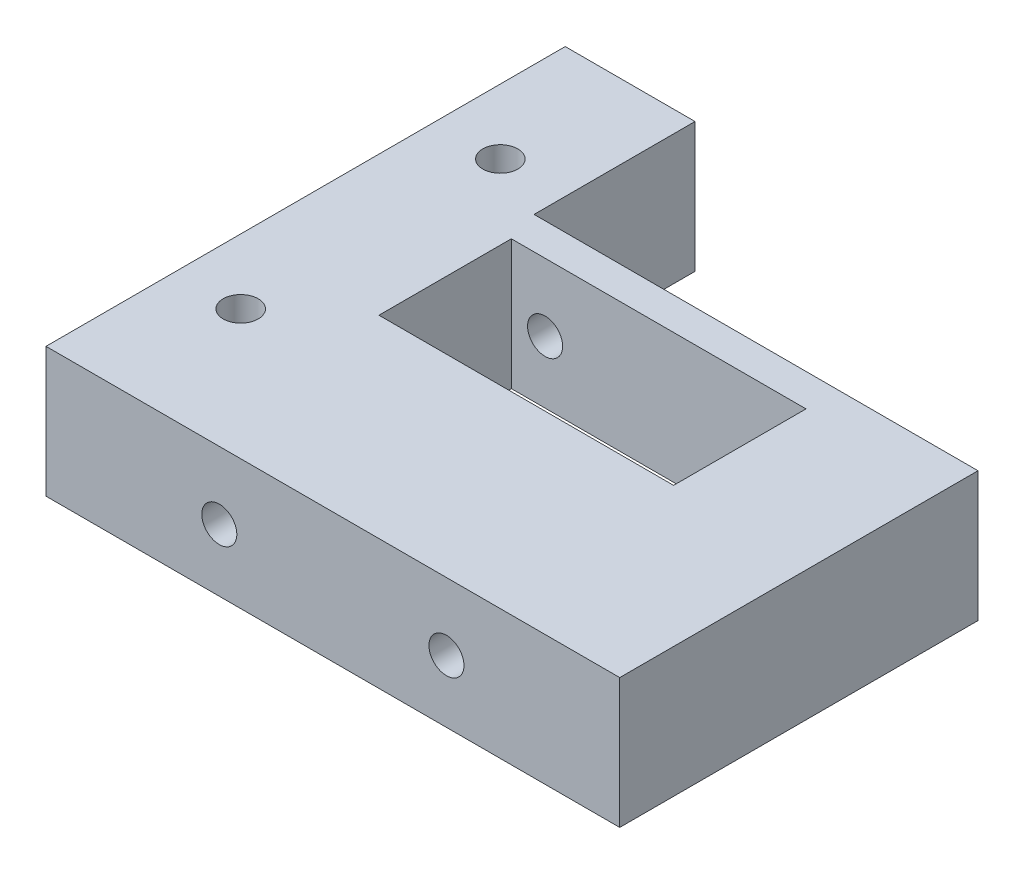
SolidWorks part; units mm, degrees
ref_plane "Front Plane" through (0, 0, 0) normal (0, 0, 1) x (1, 0, 0)
ref_plane "Top Plane" through (0, 0, 0) normal (0, 1, 0) x (1, 0, 0)
ref_plane "Right Plane" through (0, 0, 0) normal (1, 0, 0) x (0, 0, -1)
sketch "Sketch1" plane through (0, 0, 0) normal (0, 1, 0) x (1, 0, 0)
  line L1 (56.134, 50.8) -> (-56.134, 50.8)
  line L2 (56.134, 50.8) -> (56.134, -50.8)
  line L3 (56.134, -50.8) -> (-56.134, -50.8)
  line L4 (-56.134, 50.8) -> (-56.134, -50.8)
  line L5 (56.134, 50.8) -> (-56.134, -50.8) construction
  line L6 (56.134, -50.8) -> (-56.134, 50.8) construction
  line L7 (28.829, 12.954) -> (-28.829, 12.954)
  line L8 (28.829, 12.954) -> (28.829, -12.954)
  line L9 (28.829, -12.954) -> (-28.829, -12.954)
  line L10 (-28.829, 12.954) -> (-28.829, -12.954)
  line L11 (28.829, 12.954) -> (-28.829, -12.954) construction
  line L12 (28.829, -12.954) -> (-28.829, 12.954) construction
  point P0 (0, 0)
  point P6 (0, 0)
  dimension "D1" = 56.134
  dimension "D2" = 101.6
  dimension "D3" = 25.908
  dimension "D4" = 57.658
extrude "Boss-Extrude1" add sketch "Sketch1" along normal blind 25.4
sketch "Sketch2" plane through (0, 0, 0) normal (0, 1, 0) x (1, 0, 0)
  line L0 (56.134, 50.8) -> (-56.134, 50.8) construction
  line L1 (-30.734, 50.8) -> (56.134, 50.8)
  line L2 (-30.734, 50.8) -> (-30.734, 19.304)
  line L3 (-30.734, 19.304) -> (56.134, 19.304)
  line L4 (56.134, 50.8) -> (56.134, 19.304)
  line L5 (56.134, -50.8) -> (56.134, 50.8) construction
  line L6 (28.829, 12.954) -> (-28.829, 12.954) construction
  line L7 (-56.134, 50.8) -> (-56.134, -50.8) construction
  dimension "D1" = 6.35
  dimension "D2" = 25.4
extrude "Cut-Extrude1" cut sketch "Sketch2" along normal through all
sketch "Sketch4" plane through (0, 0, -19.304) normal (0, 0, -1) x (-1, 0, 0)
  circle A0 centre (-22.225, 12.1902) radius 3.429
  circle A1 centre (22.225, 12.1902) radius 3.429
  point P4 (0, 0)
  dimension "D2" = 6.858
  dimension "D1" = 44.45
  dimension "D3" = 22.225
extrude "Cut-Extrude2" cut sketch "Sketch4" against normal through all
sketch "Sketch5" plane through (0, 25.4, 0) normal (0, 1, 0) x (1, 0, 0)
  line L0 (-43.434, 50.8) -> (-43.434, -50.8) construction
  line L1 (-30.734, 50.8) -> (-56.134, 50.8) construction
  line L2 (-56.134, -50.8) -> (56.134, -50.8) construction
  circle A0 centre (-43.434, 25.4) radius 3.429
  circle A1 centre (-43.434, -25.4) radius 3.429
  point P10 (-49.0671, 22.3356)
  point P11 (0, 0)
  point P12 (-43.434, 0)
  dimension "D1" = 6.858
  dimension "D3" = 25.4
  dimension "D2" = 50.8
extrude "Cut-Extrude3" cut sketch "Sketch5" against normal through all
ref_plane "Plane1" through (0, 0, 0) normal (0, 0, -1) x (-1, 0, 0)
ref_plane "Plane2" through (0, 0, 0) normal (1, 0, 0) x (0, 0, -1)
